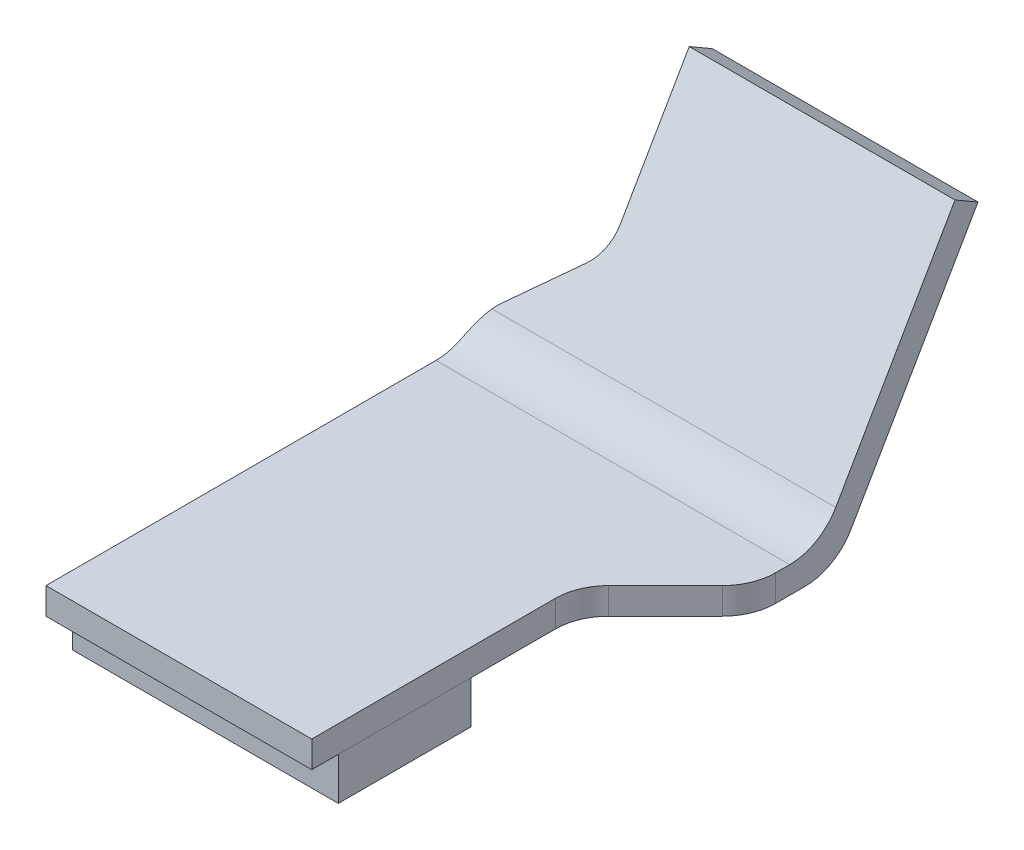
SolidWorks part; units mm, degrees
ref_plane "Front Plane" through (0, 0, 0) normal (0, 0, 1) x (1, 0, 0)
ref_plane "Top Plane" through (0, 0, 0) normal (0, 1, 0) x (1, 0, 0)
ref_plane "Right Plane" through (0, 0, 0) normal (1, 0, 0) x (0, 0, -1)
sketch "Sketch1" plane through (0, 0, 0) normal (1, 0, 0) x (0, 0, -1)
  line L0 (4.4879, 9.7733) -> (-0.5774, 1)
  line L1 (-0.5774, 1) -> (-16.4066, 1)
  line L3 (-16.4066, 0) -> (0, 0)
  line L4 (0, 0) -> (-0.5774, 1) construction
  line L5 (0, 0) -> (5.3539, 9.2733)
  line L12 (-16.4066, 0) -> (-16.4066, 1)
  line L13 (5.3539, 9.2733) -> (4.4879, 9.7733)
  dimension "D1" = 60
  dimension "D2" = 60
  dimension "D3" = 16.4066
  dimension "D4" = 10.7079
  dimension "D5" = 1
  dimension "D6" = 1
extrude "Boss-Extrude1" add sketch "Sketch1" along normal blind 13.31
sketch "Sketch2" plane through (0, 0, 0) normal (0, 1, 0) x (1, 0, 0)
  line L0 (13.31, -16.4066) -> (10, -16.4066)
  line L1 (13.31, -16.4066) -> (0, -16.4066) construction
  line L2 (10, -16.4066) -> (10, -6.4066)
  line L3 (10, -6.4066) -> (13.31, -3.0966)
  line L4 (13.31, -0.5774) -> (13.31, -16.4066) construction
  line L5 (13.31, -3.0966) -> (13.31, -16.4066)
  dimension "D1" = 45
  dimension "D3" = 10
  dimension "D4" = 10
extrude "Cut-Extrude1" cut sketch "Sketch2" along normal up to surface (1 mm away) up to face at (6.655, 1, 8.492)
sketch "Sketch3" plane through (0, 0.5, 0.866) normal (0, 0.5, 0.866) x (1, 0, 0)
  line L0 (0, 10.7079) -> (0, 1.3979)
  line L1 (0, 10.7079) -> (0, 0.5774) construction
  line L2 (0, 1.3979) -> (3.31, 4.7079)
  line L3 (3.31, 4.7079) -> (3.31, 10.7079)
  line L4 (13.31, 10.7079) -> (0, 10.7079) construction
  line L5 (3.31, 10.7079) -> (0, 10.7079)
  dimension "D1" = 10
  dimension "D2" = 45
  dimension "D3" = 6
extrude "Cut-Extrude2" cut sketch "Sketch3" against normal up to surface (1 mm away) up to face at (6.655, 4.6367, -2.677)
fillet "Fillet1" radius 2 2 edges at (6.655, 1, 0.5774) (6.655, 0, 0)
fillet "Fillet2" radius 2 4 edges at (3.31, 4.3272, -1.9209) (0, 1.4676, -0.2538) (10, 0.5, 6.4066) (13.31, 0.5, 3.0966)
sketch "Sketch4" plane through (0, 0, 0) normal (0, -1, 0) x (1, 0, 0)
  line L0 (0, 16.4066) -> (0, 1.1547) construction
  line L1 (0, 15.4066) -> (10, 15.4066)
  line L2 (0, 15.4066) -> (0, 10.4066)
  line L3 (0, 10.4066) -> (10, 10.4066)
  line L4 (10, 15.4066) -> (10, 10.4066)
  line L5 (10, 7.235) -> (10, 16.4066) construction
  line L6 (10, 16.4066) -> (0, 16.4066) construction
  dimension "D1" = 1
  dimension "D2" = 10
  dimension "D3" = 5
extrude "Boss-Extrude2" add sketch "Sketch4" along normal blind 1.6 separate body
